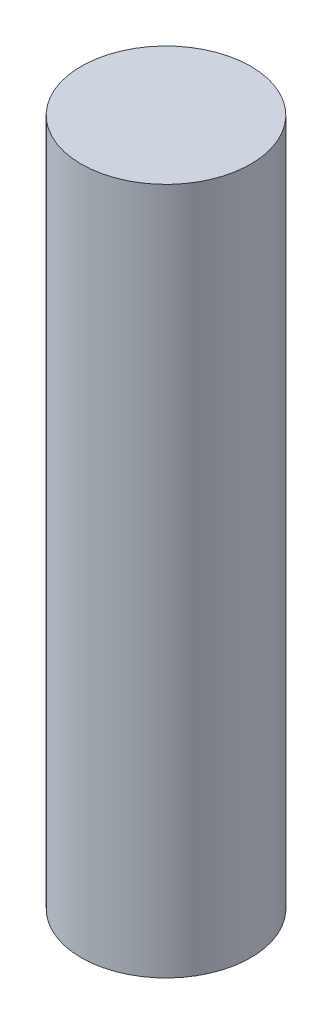
SolidWorks part; units mm, degrees
ref_plane "Front Plane" through (0, 0, 0) normal (0, 0, 1) x (1, 0, 0)
ref_plane "Top Plane" through (0, 0, 0) normal (0, 1, 0) x (1, 0, 0)
ref_plane "Right Plane" through (0, 0, 0) normal (1, 0, 0) x (0, 0, -1)
sketch "Sketch1" plane through (0, 0, 0) normal (0, 1, 0) x (1, 0, 0)
  circle A0 centre (0, 0) radius 37
  dimension "D1" = 74
extrude "Boss-Extrude1" add sketch "Sketch1" along normal blind 300
